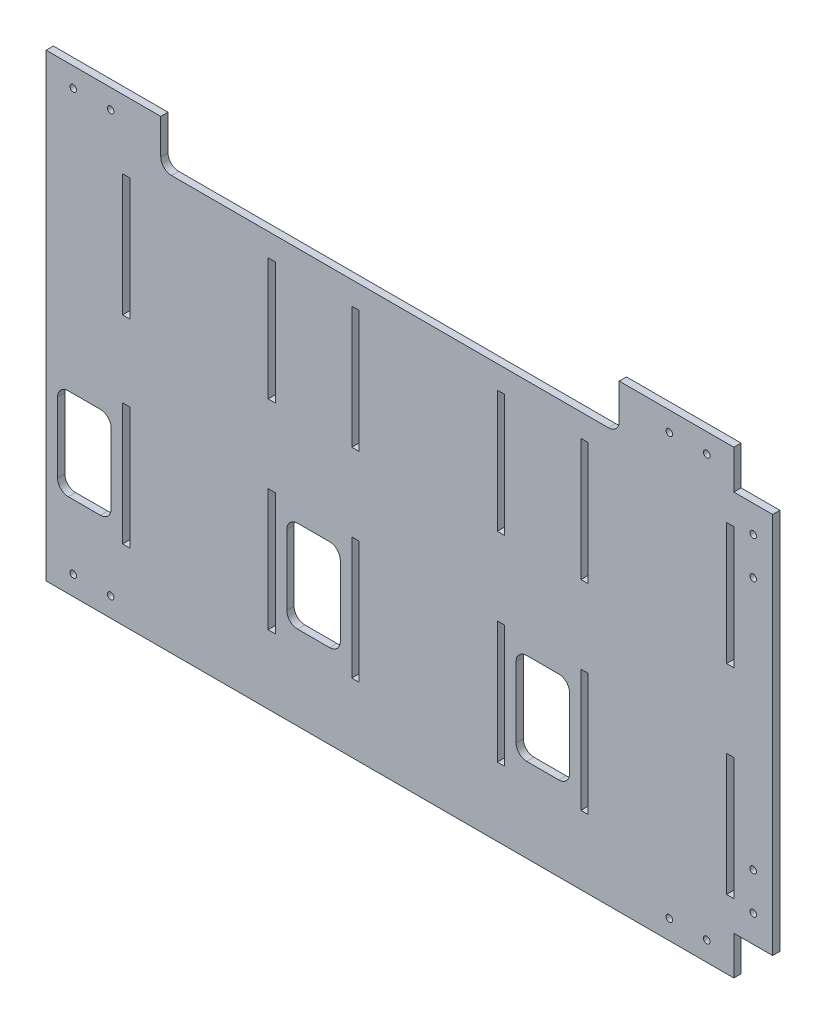
SolidWorks part; units mm, degrees
ref_plane "前基準面" through (0, 0, 0) normal (0, 0, 1) x (1, 0, 0)
ref_plane "上基準面" through (0, 0, 0) normal (0, 1, 0) x (1, 0, 0)
ref_plane "右基準面" through (0, 0, 0) normal (1, 0, 0) x (0, 0, -1)
sketch "草圖1" plane through (0, 0, 0) normal (0, 0, 1) x (1, 0, 0)
  line L1 (-250.4, 150.4) -> (250.4, 150.4)
  line L2 (-250.4, 150.4) -> (-250.4, -150.4)
  line L3 (-250.4, -150.4) -> (250.4, -150.4)
  line L4 (250.4, 150.4) -> (250.4, -150.4)
  line L5 (-250.4, 150.4) -> (250.4, -150.4) construction
  line L6 (-250.4, -150.4) -> (250.4, 150.4) construction
  point P0 (0, 0)
  dimension "D1" = 500.8
  dimension "D2" = 300.8
extrude "填料-伸長1" add sketch "草圖1" along normal blind 4.75 contours L1 L4 L3 L2
sketch "草圖2" plane through (0, 0, 0) normal (0, 0, -1) x (-1, 0, 0)
  line L0 (-225, 125) -> (-225, -125) construction
  line L1 (-250.4, 150.4) -> (-225, 150.4)
  line L2 (-250.4, 150.4) -> (-250.4, 125)
  line L3 (-250.4, 125) -> (-225, 125)
  line L4 (-225, 150.4) -> (-225, 125)
  line L5 (-250.4, -150.4) -> (-225, -150.4)
  line L6 (-250.4, -150.4) -> (-250.4, -125)
  line L7 (-250.4, -125) -> (-225, -125)
  line L8 (-225, -150.4) -> (-225, -125)
  line L9 (250.4, 150.4) -> (225, 150.4)
  line L10 (250.4, 150.4) -> (250.4, 125)
  line L12 (225, 150.4) -> (225, 125)
  line L13 (250.4, -150.4) -> (225, -150.4)
  line L14 (250.4, -150.4) -> (250.4, -125)
  line L16 (225, -150.4) -> (225, -125)
  line L17 (225, 125) -> (225, -125) construction
  line L18 (250.4, 150.4) -> (-250.4, 150.4) construction
  line L19 (-225, 105.4) -> (-220.25, 105.4)
  line L20 (-225, 105.4) -> (-225, 25.4)
  line L21 (-225, 25.4) -> (-220.25, 25.4)
  line L22 (-220.25, 105.4) -> (-220.25, 25.4)
  line L23 (-225, -25.4) -> (-220.25, -25.4)
  line L24 (-225, -25.4) -> (-225, -105.4)
  line L25 (-225, -105.4) -> (-220.25, -105.4)
  line L26 (-220.25, -25.4) -> (-220.25, -105.4)
  line L27 (250.4, -150.4) -> (-250.4, -150.4) construction
  line L30 (225, 105.4) -> (225, 25.4)
  line L34 (225, -24.4) -> (225, -104.4)
  line L44 (175, 105.4) -> (175, 25.4)
  line L45 (175, 105.4) -> (170.25, 105.4)
  line L46 (170.25, 105.4) -> (170.25, 25.4)
  line L47 (175, 25.4) -> (170.25, 25.4)
  line L48 (175, -24.4) -> (175, -104.4)
  line L49 (175, -24.4) -> (170.25, -24.4)
  line L50 (170.25, -24.4) -> (170.25, -104.4)
  line L51 (175, -104.4) -> (170.25, -104.4)
  line L52 (-129.75, 105.4) -> (-129.75, 25.4)
  line L53 (-129.75, 25.4) -> (-125, 25.4)
  line L54 (-125, 105.4) -> (-125, 25.4)
  line L55 (-129.75, 105.4) -> (-125, 105.4)
  line L60 (-75, 105.4) -> (-75, 25.4)
  line L61 (-75, 25.4) -> (-70.25, 25.4)
  line L62 (-70.25, 105.4) -> (-70.25, 25.4)
  line L63 (-75, 105.4) -> (-70.25, 105.4)
  line L68 (20.25, 105.4) -> (20.25, 25.4)
  line L69 (20.25, 25.4) -> (25, 25.4)
  line L70 (25, 105.4) -> (25, 25.4)
  line L71 (20.25, 105.4) -> (25, 105.4)
  line L80 (75, 105.4) -> (75, 25.4)
  line L81 (75, 25.4) -> (79.75, 25.4)
  line L82 (79.75, 105.4) -> (79.75, 25.4)
  line L83 (75, 105.4) -> (79.75, 105.4)
  line L84 (-250.4, 0) -> (250.4, 0) construction
  line L85 (-250.4, 150.4) -> (-250.4, -150.4) construction
  line L86 (250.4, 150.4) -> (250.4, -150.4) construction
  line L87 (225, 125) -> (225, -125)
  line L89 (250.4, -125) -> (250.4, 125)
  line L91 (250.4, 125) -> (250.4, -125)
  line L92 (75, -105.4) -> (79.75, -105.4)
  line L93 (79.75, -105.4) -> (79.75, -25.4)
  line L94 (75, -25.4) -> (79.75, -25.4)
  line L95 (75, -105.4) -> (75, -25.4)
  line L96 (20.25, -105.4) -> (25, -105.4)
  line L97 (25, -105.4) -> (25, -25.4)
  line L98 (20.25, -25.4) -> (25, -25.4)
  line L99 (20.25, -105.4) -> (20.25, -25.4)
  line L101 (-129.75, -105.4) -> (-125, -105.4)
  line L102 (-125, -105.4) -> (-125, -25.4)
  line L103 (-129.75, -25.4) -> (-125, -25.4)
  line L104 (-129.75, -105.4) -> (-129.75, -25.4)
  line L105 (-75, -105.4) -> (-70.25, -105.4)
  line L106 (-70.25, -105.4) -> (-70.25, -25.4)
  line L107 (-75, -25.4) -> (-70.25, -25.4)
  line L108 (-75, -105.4) -> (-75, -25.4)
  line M9 (250.4, -150.4) -> (250.4, 150.4)
  line M10 (250.4, 150.4) -> (-250.4, 150.4)
  line M12 (-250.4, -150.4) -> (250.4, -150.4)
  dimension "D1" = 25.4
  dimension "D2" = 25.4
  dimension "D3" = 25.4
  dimension "D4" = 25.4
  dimension "D5" = 25.4
  dimension "D6" = 25.4
  dimension "D7" = 25.4
  dimension "D8" = 25.4
  dimension "D9" = 4.75
  dimension "D10" = 80
  dimension "D11" = 45
  dimension "D12" = 4.75
  dimension "D13" = 80
  dimension "D14" = 45
  dimension "D15" = 50
  dimension "D16" = 100
  dimension "D17" = 25.4
  dimension "D18" = 25.4
  dimension "D19" = 250
  dimension "D20" = 50
  dimension "D27" = 50
  dimension "D21" = 4.75
  dimension "D23" = 4.75
  dimension "D28" = 100
  dimension "D22" = 2
  dimension "D24" = 2
  dimension "D25" = 2
  dimension "D26" = 2
extrude "除料-伸長1" cut sketch "草圖2" against normal blind 10 contours L12 L87 L30 L34 L16 M12 M9 M10 | L104 L101 L102 L103 | L108 L105 L106 L107
sketch "草圖3" plane through (0, 0, 4.75) normal (0, 0, 1) x (1, 0, 0)
  circle A0 centre (-207.3, 137.7) radius 2.15
  circle A1 centre (-182.8, 137.7) radius 2.15
  circle A2 centre (182.8, 137.7) radius 2.15
  circle A3 centre (207.3, 137.7) radius 2.15
  circle A4 centre (237.7, 107.3) radius 2.15
  circle A5 centre (237.7, 82.8) radius 2.15
  circle A6 centre (237.7, -82.8) radius 2.15
  circle A7 centre (237.7, -107.3) radius 2.15
  circle A8 centre (207.3, -137.7) radius 2.15
  circle A9 centre (182.8, -137.7) radius 2.15
  circle A10 centre (-207.3, -137.7) radius 2.15
  circle A11 centre (-182.8, -137.7) radius 2.15
extrude "除料-伸長2" cut sketch "草圖3" against normal blind 5
sketch "草圖5" plane through (0, 0, 4.75) normal (0, 0, 1) x (1, 0, 0)
  line L0 (-75, 25.4) -> (-75, 105.4) construction
  line L1 (82.5, -35.4) -> (117.5, -35.4)
  line L2 (82.5, -35.4) -> (82.5, -95.4)
  line L3 (82.5, -95.4) -> (117.5, -95.4)
  line L4 (117.5, -35.4) -> (117.5, -95.4)
  line L5 (82.5, -35.4) -> (117.5, -95.4) construction
  line L6 (82.5, -95.4) -> (117.5, -35.4) construction
  line L7 (-67.5, -35.4) -> (-32.5, -35.4)
  line L8 (-67.5, -35.4) -> (-67.5, -95.4)
  line L9 (-67.5, -95.4) -> (-32.5, -95.4)
  line L10 (-32.5, -35.4) -> (-32.5, -95.4)
  line L11 (-67.5, -35.4) -> (-32.5, -95.4) construction
  line L12 (-67.5, -95.4) -> (-32.5, -35.4) construction
  line L13 (-217.5, -35.4) -> (-182.5, -35.4)
  line L14 (-217.5, -35.4) -> (-217.5, -95.4)
  line L15 (-217.5, -95.4) -> (-182.5, -95.4)
  line L16 (-182.5, -35.4) -> (-182.5, -95.4)
  line L17 (-217.5, -35.4) -> (-182.5, -95.4) construction
  line L18 (-217.5, -95.4) -> (-182.5, -35.4) construction
  line L19 (-175, 25.4) -> (-175, 105.4) construction
  line L22 (-225, 150.4) -> (225, 150.4) construction
  line L23 (125, 25.4) -> (125, 105.4) construction
  line L24 (225, 125) -> (225, 150.4) construction
  line L25 (-150, 150.4) -> (150, 150.4)
  line L26 (-150, 150.4) -> (-150, 120.4)
  line L27 (-150, 120.4) -> (150, 120.4)
  line L28 (150, 150.4) -> (150, 120.4)
  line L29 (-225, -150.4) -> (225, -150.4) construction
  point P0 (100, -65.4)
  point P5 (-50, -65.4)
  point P10 (-200, -65.4)
  dimension "D1" = 35
  dimension "D2" = 60
  dimension "D3" = 35
  dimension "D4" = 60
  dimension "D5" = 35
  dimension "D6" = 60
  dimension "D7" = 7.5
  dimension "D8" = 7.5
  dimension "D9" = 55
  dimension "D10" = 55
  dimension "D11" = 55
  dimension "D12" = 7.5
  dimension "D13" = 300
  dimension "D14" = 75
  dimension "D15" = 30
extrude "除料-伸長3" cut sketch "草圖5" against normal blind 10
fillet "圓角1" radius 7 14 edges at (-150, 120.4, 2.375) (150, 120.4, 2.375) (117.5, -35.4, 2.375) (82.5, -35.4, 2.375) (82.5, -95.4, 2.375) (117.5, -95.4, 2.375) (-32.5, -95.4, 2.375) (-67.5, -95.4, 2.375) (-32.5, -35.4, 2.375) (-67.5, -35.4, 2.375) (-182.5, -95.4, 2.375) (-217.5, -95.4, 2.375) (-217.5, -35.4, 2.375) (-182.5, -35.4, 2.375)
